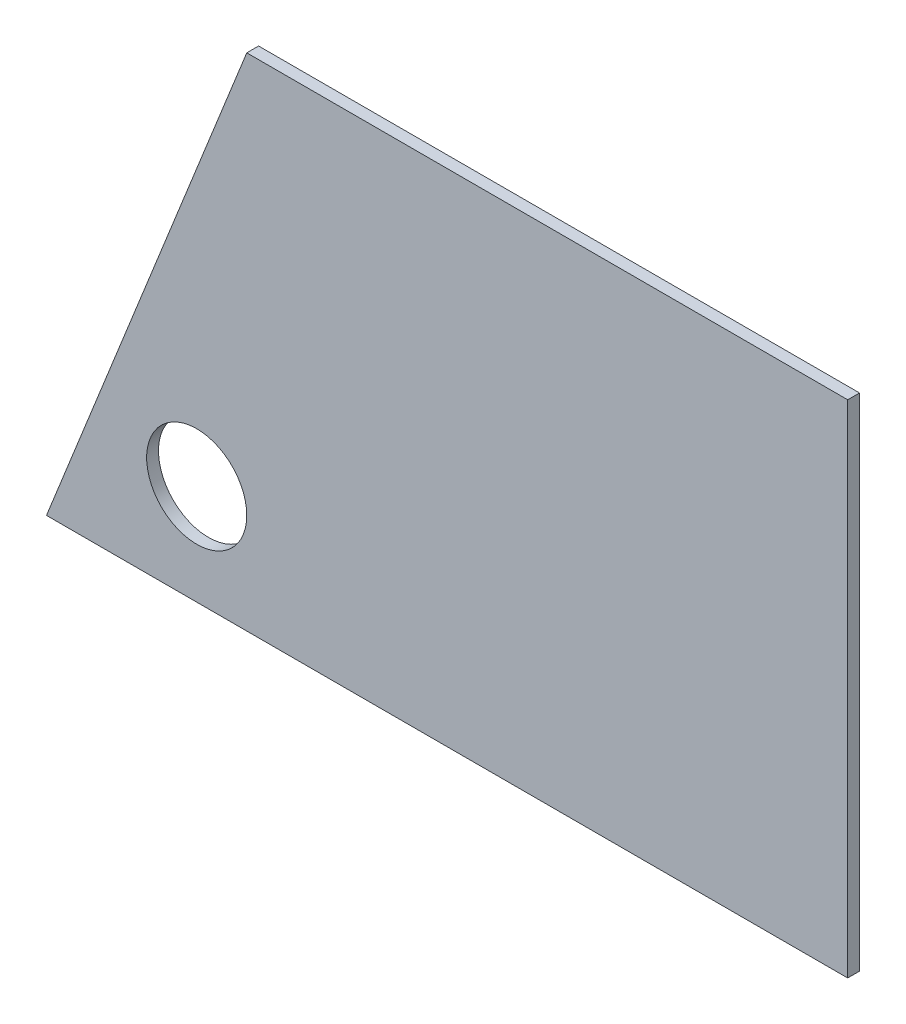
SolidWorks part; units mm, degrees
ref_plane "Front Plane" through (0, 0, 0) normal (0, 0, 1) x (1, 0, 0)
ref_plane "Top Plane" through (0, 0, 0) normal (0, 1, 0) x (1, 0, 0)
ref_plane "Right Plane" through (0, 0, 0) normal (1, 0, 0) x (0, 0, -1)
sketch "Sketch2" plane through (0, 0, 0) normal (0, 0, 1) x (1, 0, 0)
  line L0 (0, 0) -> (203.2, 0)
  line L1 (203.2, 0) -> (203.2, 127)
  line L2 (203.2, 127) -> (50.8, 127)
  line L3 (50.8, 127) -> (0, 0)
  line L4 (38.1, 25.4) -> (38.1, 0) construction
  line L5 (38.1, 0) -> (0, 0)
  circle A0 centre (38.1, 25.4) radius 12.6939
  dimension "D1" = 203.2
  dimension "D2" = 127
  dimension "D3" = 152.4
  dimension "D4" = 38.1
  dimension "D5" = 25.4
extrude "Boss-Extrude1" add sketch "Sketch2" along normal blind 3
